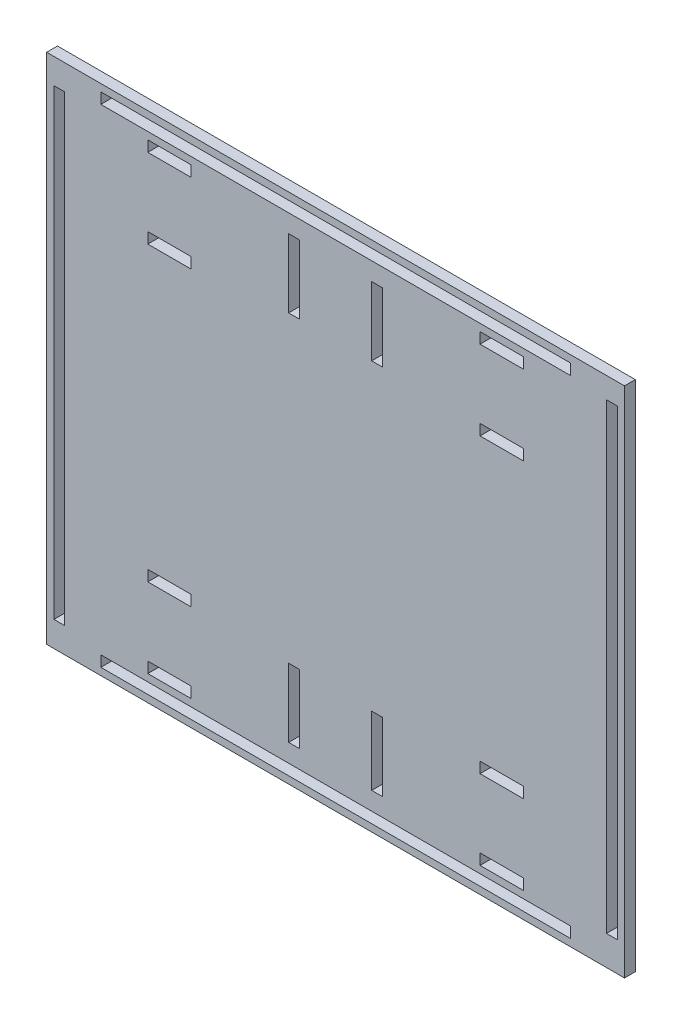
SolidWorks part; units mm, degrees
ref_plane "Front Plane" through (0, 0, 0) normal (0, 0, 1) x (1, 0, 0)
ref_plane "Top Plane" through (0, 0, 0) normal (0, 1, 0) x (1, 0, 0)
ref_plane "Right Plane" through (0, 0, 0) normal (1, 0, 0) x (0, 0, -1)
sketch "Sketch1" plane through (0, 0, 0) normal (0, 0, 1) x (1, 0, 0)
  line L0 (-67.654, -87.4973) -> (62.346, -87.4973)
  line L1 (-82.654, 49.5027) -> (77.346, 49.5027)
  line L2 (-82.654, 49.5027) -> (-82.654, -92.4973)
  line L3 (-82.654, -92.4973) -> (77.346, -92.4973)
  line L4 (77.346, 49.5027) -> (77.346, -92.4973)
  line L5 (-67.654, 47.5027) -> (62.346, 47.5027)
  line L6 (-67.654, 47.5027) -> (-67.654, 44.5027)
  line L7 (-67.654, 44.5027) -> (62.346, 44.5027)
  line L8 (62.346, 47.5027) -> (62.346, 44.5027)
  line L9 (-67.654, -87.4973) -> (-67.654, -90.4973)
  line L10 (-67.654, -90.4973) -> (62.346, -90.4973)
  line L11 (62.346, -87.4973) -> (62.346, -90.4973)
  line L13 (-80.654, 42.5027) -> (-77.654, 42.5027)
  line L14 (-80.654, 42.5027) -> (-80.654, -85.4973)
  line L15 (-80.654, -85.4973) -> (-77.654, -85.4973)
  line L16 (-77.654, 42.5027) -> (-77.654, -85.4973)
  line L20 (72.346, 43.6925) -> (75.346, 43.6925)
  line L21 (72.346, 43.6925) -> (72.346, -84.3075)
  line L22 (72.346, -84.3075) -> (75.346, -84.3075)
  line L23 (75.346, 43.6925) -> (75.346, -84.3075)
  line L25 (37.346, -60.4973) -> (49.346, -60.4973)
  line L30 (37.346, -82.4973) -> (49.346, -82.4973)
  line L31 (37.346, -82.4973) -> (37.346, -85.4973)
  line L32 (37.346, -85.4973) -> (49.346, -85.4973)
  line L33 (49.346, -82.4973) -> (49.346, -85.4973)
  line L34 (37.346, -60.4973) -> (37.346, -63.4973)
  line L35 (37.346, -63.4973) -> (49.346, -63.4973)
  line L36 (49.346, -60.4973) -> (49.346, -63.4973)
  line L46 (37.346, 42.5027) -> (49.346, 42.5027)
  line L47 (7.346, -63.4973) -> (10.346, -63.4973)
  line L48 (7.346, -63.4973) -> (7.346, -82.4973)
  line L49 (7.346, -82.4973) -> (10.346, -82.4973)
  line L50 (10.346, -63.4973) -> (10.346, -82.4973)
  line L51 (49.346, 39.5027) -> (49.346, 42.5027)
  line L52 (37.346, 39.5027) -> (49.346, 39.5027)
  line L53 (37.346, 39.5027) -> (37.346, 42.5027)
  line L54 (37.346, 17.5027) -> (37.346, 20.5027)
  line L55 (37.346, 20.5027) -> (49.346, 20.5027)
  line L56 (49.346, 17.5027) -> (49.346, 20.5027)
  line L57 (37.346, 17.5027) -> (49.346, 17.5027)
  line L58 (7.346, 39.5027) -> (10.346, 39.5027)
  line L59 (10.346, 20.5027) -> (10.346, 39.5027)
  line L60 (7.346, 20.5027) -> (10.346, 20.5027)
  line L61 (7.346, 20.5027) -> (7.346, 39.5027)
  line L62 (-12.654, -82.4973) -> (-15.654, -82.4973)
  line L63 (-15.654, -63.4973) -> (-15.654, -82.4973)
  line L64 (-12.654, -63.4973) -> (-15.654, -63.4973)
  line L65 (-12.654, -63.4973) -> (-12.654, -82.4973)
  line L66 (-42.654, -85.4973) -> (-54.654, -85.4973)
  line L67 (-54.654, -82.4973) -> (-54.654, -85.4973)
  line L68 (-42.654, -82.4973) -> (-54.654, -82.4973)
  line L69 (-42.654, -82.4973) -> (-42.654, -85.4973)
  line L70 (-42.654, -60.4973) -> (-42.654, -63.4973)
  line L71 (-42.654, -63.4973) -> (-54.654, -63.4973)
  line L72 (-54.654, -60.4973) -> (-54.654, -63.4973)
  line L73 (-42.654, -60.4973) -> (-54.654, -60.4973)
  line L74 (-42.654, 17.5027) -> (-54.654, 17.5027)
  line L75 (-54.654, 17.5027) -> (-54.654, 20.5027)
  line L76 (-42.654, 20.5027) -> (-54.654, 20.5027)
  line L77 (-42.654, 17.5027) -> (-42.654, 20.5027)
  line L78 (-42.654, 39.5027) -> (-42.654, 42.5027)
  line L79 (-42.654, 39.5027) -> (-54.654, 39.5027)
  line L80 (-54.654, 39.5027) -> (-54.654, 42.5027)
  line L81 (-42.654, 42.5027) -> (-54.654, 42.5027)
  line L82 (-12.654, 20.5027) -> (-12.654, 39.5027)
  line L83 (-12.654, 20.5027) -> (-15.654, 20.5027)
  line L84 (-15.654, 20.5027) -> (-15.654, 39.5027)
  line L85 (-12.654, 39.5027) -> (-15.654, 39.5027)
  point P12 (62.346, -88.9973)
  dimension "D1" = 160
  dimension "D2" = 142
  dimension "D3" = 130
  dimension "D4" = 3
  dimension "D5" = 15
  dimension "D6" = 2
  dimension "D7" = 15
  dimension "D8" = 130
  dimension "D9" = 3
  dimension "D10" = 128
  dimension "D11" = 2
  dimension "D12" = 7
  dimension "D13" = 2
  dimension "D14" = 5.8101
  dimension "D15" = 12
  dimension "D16" = 3
  dimension "D17" = 23
  dimension "D18" = 2
  dimension "D19" = 19
  dimension "D20" = 23
  dimension "D21" = 19
  dimension "D22" = 3
  dimension "D23" = 12
  dimension "D24" = 27
  dimension "D25" = 2
  dimension "D26" = 2
  dimension "D27" = 19
  dimension "D28" = 19
  dimension "D29" = 3
  dimension "D30" = 3
  dimension "D31" = 2
  dimension "D32" = 3
  dimension "D33" = 5
  dimension "D34" = 5
  dimension "D35" = 5
extrude "Boss-Extrude1" add sketch "Sketch1" along normal blind 3
